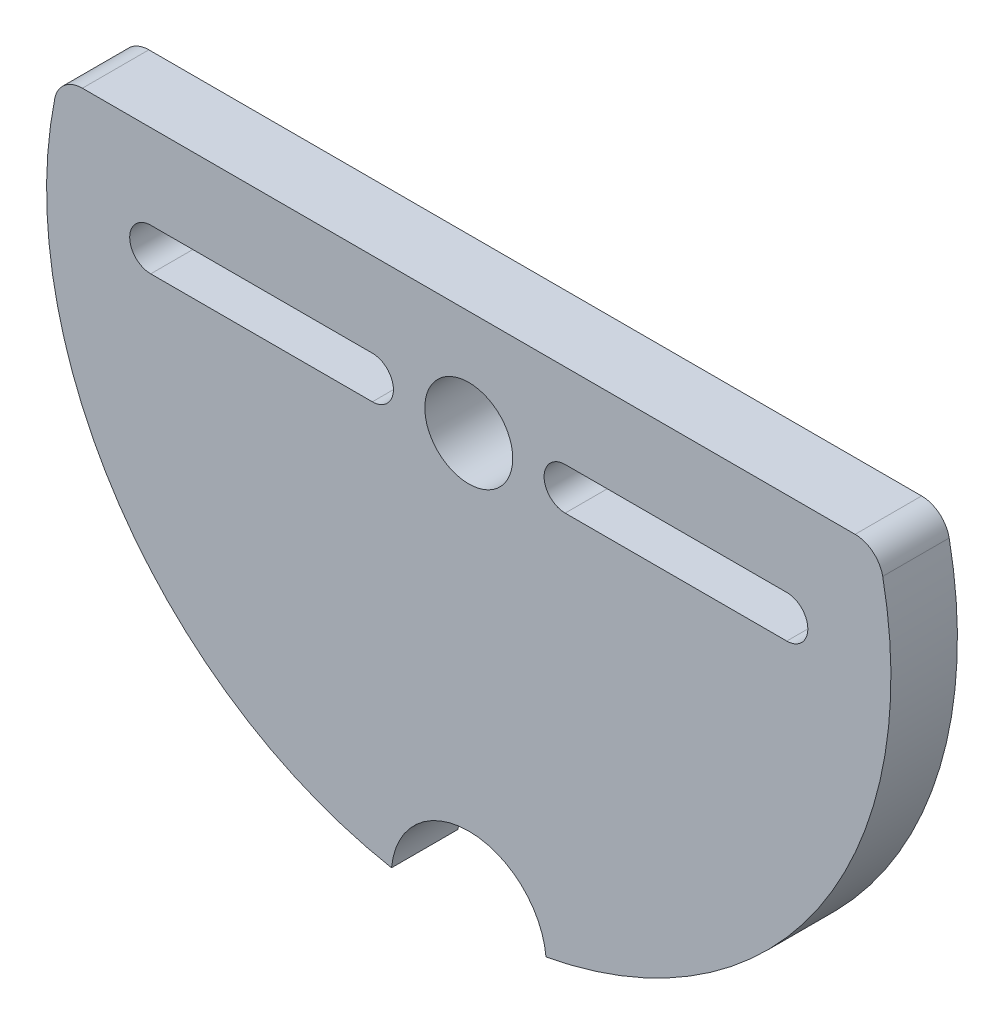
SolidWorks part; units mm, degrees
ref_plane "Front Plane" through (0, 0, 0) normal (0, 0, 1) x (1, 0, 0)
ref_plane "Top Plane" through (0, 0, 0) normal (0, 1, 0) x (1, 0, 0)
ref_plane "Right Plane" through (0, 0, 0) normal (1, 0, 0) x (0, 0, -1)
sketch "Sketch1" plane through (0, 0, 0) normal (0, 0, 1) x (1, 0, 0)
  line L1 (0, 0) -> (0, -19.05) construction
  line L2 (-3.4852, -18.7285) -> (0, -19.05) construction
  line L3 (17.4336, 4.7625) -> (-17.4336, 4.7625)
  arc A1 (-18.6789, 3.742) -> (-3.4852, -18.7285) centre (0, 0) ccw
  arc A2 (-3.4852, -18.7285) -> (3.4852, -18.7285) centre (0, -19.05) cw
  arc A3 (-17.4336, 4.7625) -> (-18.6789, 3.742) centre (-17.4336, 3.4925) ccw
  arc A5 (18.6789, 3.742) -> (3.4852, -18.7285) centre (0, 0) cw
  arc A6 (17.4336, 4.7625) -> (18.6789, 3.742) centre (17.4336, 3.4925) cw
  point P4 (0, 0)
  point P7 (17.4746, 3.175)
  dimension "D1" = 3.5
  dimension "D3" = 19.05
  dimension "D4" = 1.27
  dimension "D2" = 4.7625
extrude "Boss-Extrude1" add sketch "Sketch1" along normal blind 3
sketch "Sketch4" plane through (0, 0, 3) normal (0, 0, 1) x (1, 0, 0)
  line L0 (-14.35, 0) -> (-4.35, 0) construction
  line L1 (-14.35, 0.95) -> (-4.35, 0.95)
  line L2 (-14.35, -0.95) -> (-4.35, -0.95)
  line L3 (4.35, 0) -> (14.35, 0) construction
  line L4 (4.35, 0.95) -> (14.35, 0.95)
  line L5 (4.35, -0.95) -> (14.35, -0.95)
  line L6 (-4.35, 0) -> (4.35, 0) construction
  line L7 (-4.35, 0.95) -> (4.35, 0.95) construction
  arc A0 (-14.35, 0.95) -> (-14.35, -0.95) centre (-14.35, 0) ccw
  arc A1 (-4.35, -0.95) -> (-4.35, 0.95) centre (-4.35, 0) ccw
  arc A2 (4.35, 0.95) -> (4.35, -0.95) centre (4.35, 0) ccw
  arc A3 (14.35, -0.95) -> (14.35, 0.95) centre (14.35, 0) ccw
  circle A4 centre (0, 0) radius 1.9844
  point P3 (-9.35, 0)
  point P8 (9.35, 0)
  point P17 (0, 0)
  dimension "D4" = 3.9688
  dimension "D1" = 28.7
  dimension "D2" = 1.9
  dimension "D3" = 8.7
extrude "Cut-Extrude2" cut sketch "Sketch4" against normal through all
